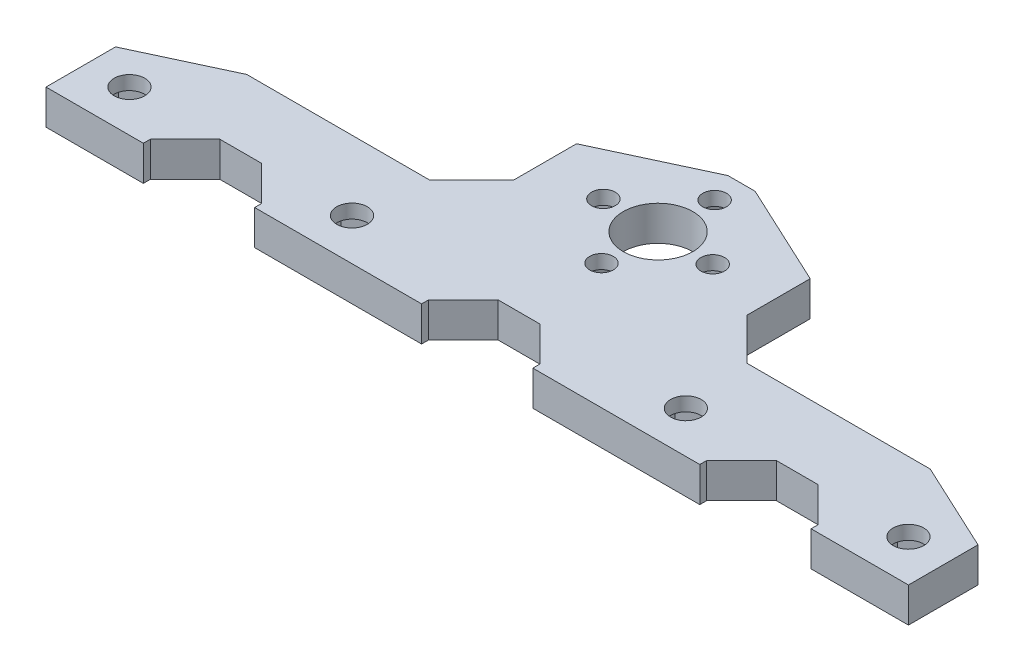
SolidWorks part; units mm, degrees
ref_plane "Front Plane" through (0, 0, 0) normal (0, 0, 1) x (1, 0, 0)
ref_plane "Top Plane" through (0, 0, 0) normal (0, 1, 0) x (1, 0, 0)
ref_plane "Right Plane" through (0, 0, 0) normal (1, 0, 0) x (0, 0, -1)
sketch "Sketch1" plane through (0, 139.1735, 0) normal (0, -1, 0) x (1, 0, 0)
  line L0 (-19.5638, 131.6186) -> (-13.5638, 131.6186) construction
  line L1 (152.4362, 89.6186) -> (28.4362, 89.6186)
  line L2 (152.4362, 89.6186) -> (152.4362, 131.6186)
  line L3 (152.4362, 131.6186) -> (28.4362, 131.6186)
  line L4 (28.4362, 89.6186) -> (28.4362, 131.6186)
  line L6 (87.3419, 93.6198) -> (88.9585, 90.8198)
  line L7 (98.435, 98.5243) -> (101.235, 100.1409)
  line L8 (101.235, 100.1409) -> (101.235, 103.374)
  line L9 (101.235, 103.374) -> (98.435, 104.9906)
  line L10 (98.435, 104.9906) -> (95.635, 103.374)
  line L11 (95.635, 103.374) -> (95.635, 100.1409)
  line L12 (95.635, 100.1409) -> (98.435, 98.5243)
  line L13 (88.9585, 90.8198) -> (92.1917, 90.8198)
  line L14 (92.1917, 90.8198) -> (93.8082, 93.6198)
  line L15 (93.8082, 93.6198) -> (92.1917, 96.4198)
  line L16 (92.1917, 96.4198) -> (88.9585, 96.4198)
  line L17 (88.9585, 96.4198) -> (87.3419, 93.6198)
  line L18 (82.4374, 104.7129) -> (79.6374, 103.0963)
  line L19 (79.6374, 103.0963) -> (79.6374, 99.8631)
  line L20 (79.6374, 99.8631) -> (82.4374, 98.2466)
  line L21 (82.4374, 98.2466) -> (85.2374, 99.8631)
  line L22 (85.2374, 99.8631) -> (85.2374, 103.0963)
  line L23 (85.2374, 103.0963) -> (82.4374, 104.7129)
  line L24 (93.5305, 109.6174) -> (91.9139, 112.4174)
  line L25 (91.9139, 112.4174) -> (88.6808, 112.4174)
  line L26 (88.6808, 112.4174) -> (87.0642, 109.6174)
  line L27 (87.0642, 109.6174) -> (88.6808, 106.8174)
  line L28 (88.6808, 106.8174) -> (91.9139, 106.8174)
  line L29 (91.9139, 106.8174) -> (93.5305, 109.6174)
  line L30 (34.4362, 121.6186) -> (66.4362, 121.6186) construction
  line L31 (34.4362, 125.891) -> (30.7362, 123.7548)
  line L32 (30.7362, 123.7548) -> (30.7362, 119.4824)
  line L33 (30.7362, 119.4824) -> (34.4362, 117.3462)
  line L34 (34.4362, 117.3462) -> (38.1362, 119.4824)
  line L35 (38.1362, 119.4824) -> (38.1362, 123.7548)
  line L36 (38.1362, 123.7548) -> (34.4362, 125.891)
  line L38 (62.7362, 123.7548) -> (62.7362, 119.4824)
  line L39 (62.7362, 119.4824) -> (66.4362, 117.3462)
  line L40 (66.4362, 117.3462) -> (70.1362, 119.4824)
  line L41 (70.1362, 119.4824) -> (70.1362, 123.7548)
  line L42 (70.1362, 123.7548) -> (66.4362, 125.891)
  line L43 (66.4362, 125.891) -> (62.7362, 123.7548)
  line L44 (118.1362, 123.7548) -> (114.4362, 125.891)
  line L45 (114.4362, 125.891) -> (110.7362, 123.7548)
  line L46 (110.7362, 123.7548) -> (110.7362, 119.4824)
  line L47 (110.7362, 119.4824) -> (114.4362, 117.3462)
  line L48 (114.4362, 117.3462) -> (118.1362, 119.4824)
  line L49 (118.1362, 119.4824) -> (118.1362, 123.7548)
  line L50 (142.7362, 119.4824) -> (146.4362, 117.3462)
  line L51 (146.4362, 117.3462) -> (150.1362, 119.4824)
  line L52 (150.1362, 119.4824) -> (150.1362, 123.7548)
  line L53 (150.1362, 123.7548) -> (146.4362, 125.891)
  line L54 (146.4362, 125.891) -> (142.7362, 123.7548)
  line L55 (142.7362, 123.7548) -> (142.7362, 119.4824)
  circle A0 centre (146.4362, 121.6186) radius 3.75 construction
  circle A1 centre (34.4362, 121.6186) radius 3.75 construction
  circle A3 centre (98.435, 101.7574) radius 2.8 construction
  circle A5 centre (34.4362, 121.6186) radius 3.7 construction
  circle A6 centre (66.4362, 121.6186) radius 3.7 construction
  circle A7 centre (114.4362, 121.6186) radius 3.7 construction
  circle A8 centre (146.4362, 121.6186) radius 3.7 construction
  dimension "D3" = 6
  dimension "D4" = 5.6
  dimension "D2" = 6
  dimension "D6" = 7.4
  dimension "D7" = 0
  dimension "D8" = 7.4
  dimension "D9" = 0
  dimension "D10" = 7.4
  dimension "D11" = 0
  dimension "D12" = 7.4
  dimension "D13" = 0
  dimension "D5" = 4
extrude "Boss-Extrude1" add sketch "Sketch1" along normal blind 5
sketch "Sketch2" plane through (0, 139.1735, 0) normal (0, 1, 0) x (1, 0, 0)
  circle A0 centre (90.4362, -101.6186) radius 5
  dimension "D1" = 10
extrude "Cut-Extrude1" cut sketch "Sketch2" against normal blind 5
sketch "Sketch3" plane through (0, 139.1735, 0) normal (0, 1, 0) x (1, 0, 0)
  line L1 (28.4362, -89.6186) -> (152.4362, -89.6186)
  line L2 (28.4362, -89.6186) -> (28.4362, -131.6186)
  line L3 (28.4362, -131.6186) -> (152.4362, -131.6186)
  line L4 (152.4362, -89.6186) -> (152.4362, -131.6186)
  circle A0 centre (34.4362, -121.6186) radius 2.2
  circle A1 centre (66.4362, -121.6186) radius 2.2
  circle A2 centre (114.4362, -121.6186) radius 2.2
  circle A3 centre (146.4362, -121.6186) radius 2.2
  circle A4 centre (90.5751, -93.6198) radius 1.7
  circle A5 centre (82.4374, -101.4797) radius 1.7
  circle A6 centre (90.2974, -109.6174) radius 1.7
  circle A7 centre (98.435, -101.7574) radius 1.7
  circle A8 centre (90.4362, -101.6186) radius 5
  dimension "D1" = 10
  dimension "D2" = 4.4
  dimension "D3" = 4.4
  dimension "D4" = 4.4
  dimension "D5" = 4.4
  dimension "D6" = 3.4
  dimension "D7" = 3.4
  dimension "D8" = 3.4
  dimension "D9" = 3.4
extrude "Boss-Extrude2" add sketch "Sketch3" against normal blind 2
chamfer "Chamfer1" distance 28 angle 65 2 edges at (152.4362, 136.6735, 89.6186) (28.4362, 136.6735, 89.6186)
sketch "Sketch4" plane through (0, 134.1735, 0) normal (0, -1, 0) x (1, 0, 0)
  line L0 (152.4362, 131.6186) -> (28.4362, 131.6186) construction
  line L1 (42.4362, 131.6186) -> (58.4362, 131.6186)
  line L2 (42.4362, 131.6186) -> (42.4362, 126.6186)
  line L3 (47.4362, 121.6186) -> (53.4362, 121.6186)
  line L4 (58.4362, 131.6186) -> (58.4362, 126.6186)
  line L5 (42.4362, 126.6186) -> (47.4362, 121.6186)
  line L6 (53.4362, 121.6186) -> (58.4362, 126.6186)
  circle A0 centre (34.4362, 121.6186) radius 2.2 construction
  circle A1 centre (66.4362, 121.6186) radius 2.2 construction
  point P1 (58.4362, 121.6186)
  point P2 (42.4362, 121.6186)
  dimension "D3" = 8
  dimension "D1" = 8
  dimension "D2" = 10
extrude "Cut-Extrude2" cut sketch "Sketch4" against normal blind 10
pattern_linear "LPattern1" count 3 spacing 40 along (1, 0, 0) of "Cut-Extrude2"
sketch "Sketch5" plane through (0, 134.1735, 0) normal (0, -1, 0) x (1, 0, 0)
  line L0 (152.4362, 117.6186) -> (152.4362, 131.6186) construction
  line L1 (28.4362, 131.6186) -> (152.4362, 131.6186)
  line L2 (28.4362, 131.6186) -> (28.4362, 127.6186)
  line L3 (28.4362, 127.6186) -> (152.4362, 127.6186)
  line L4 (152.4362, 131.6186) -> (152.4362, 127.6186)
  dimension "D1" = 4
extrude "Cut-Extrude3" cut sketch "Sketch5" against normal blind 10
sketch "Sketch6" plane through (0, 134.1735, 0) normal (0, -1, 0) x (1, 0, 0)
  line L0 (41.3033, 111.6186) -> (73.6374, 111.6186)
  line L1 (28.4362, 117.6186) -> (88.4824, 89.6186) construction
  line L2 (73.6374, 111.6186) -> (73.6374, 96.5409)
  line L3 (73.6374, 96.5409) -> (41.3033, 111.6186)
  line L4 (47.4362, 121.6186) -> (53.4362, 121.6186) construction
  line L5 (79.6374, 103.0963) -> (79.6374, 99.8631) construction
  line L6 (90.4362, 121.6186) -> (90.4362, 114.5684) construction
  line L7 (87.4362, 121.6186) -> (93.4362, 121.6186) construction
  line L8 (107.235, 111.6186) -> (107.235, 96.5409)
  line L9 (139.5692, 111.6186) -> (107.235, 111.6186)
  line L10 (107.235, 96.5409) -> (139.5692, 111.6186)
  dimension "D1" = 10
  dimension "D2" = 6
extrude "Cut-Extrude4" cut sketch "Sketch6" against normal blind 10
chamfer "Chamfer2" distance 6 angle 45 2 edges at (73.6374, 136.6735, 111.6186) (107.235, 136.6735, 111.6186)
